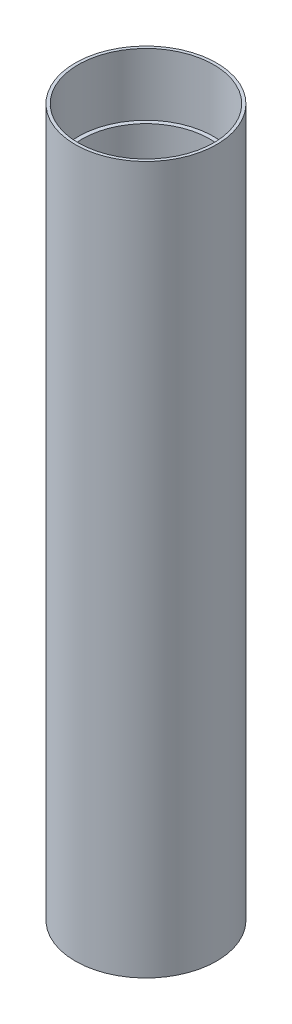
SolidWorks part; units mm, degrees
ref_plane "Спереди" through (0, 0, 0) normal (0, 0, 1) x (1, 0, 0)
ref_plane "Сверху" through (0, 0, 0) normal (0, 1, 0) x (1, 0, 0)
ref_plane "Справа" through (0, 0, 0) normal (1, 0, 0) x (0, 0, -1)
sketch "Эскиз1" plane through (0, 0, 0) normal (0, 1, 0) x (1, 0, 0)
  circle A0 centre (0, 0) radius 25
  circle A1 centre (0, 0) radius 22.5
  dimension "D1" = 50
  dimension "D2" = 45
extrude "Бобышка-Вытянуть1" add sketch "Эскиз1" along normal blind 250
sketch "Эскиз2" plane through (0, 0, 0) normal (0, -1, 0) x (1, 0, 0)
  circle A0 centre (0, 0) radius 24
  dimension "D1" = 48
extrude "Вырез-Вытянуть1" cut sketch "Эскиз2" against normal blind 22
sketch "Эскиз3" plane through (0, 250, 0) normal (0, 1, 0) x (1, 0, 0)
  circle A0 centre (0, 0) radius 24
  dimension "D1" = 48
extrude "Вырез-Вытянуть2" cut sketch "Эскиз3" against normal blind 22
sketch "Эскиз4" plane through (0, 228, 0) normal (0, 1, 0) x (1, 0, 0)
  circle A0 centre (0, 0) radius 24
  circle A1 centre (0, 0) radius 23.95
  dimension "D1" = 48
  dimension "D2" = 47.9
extrude "Бобышка-Вытянуть2" add sketch "Эскиз4" along normal blind 22
